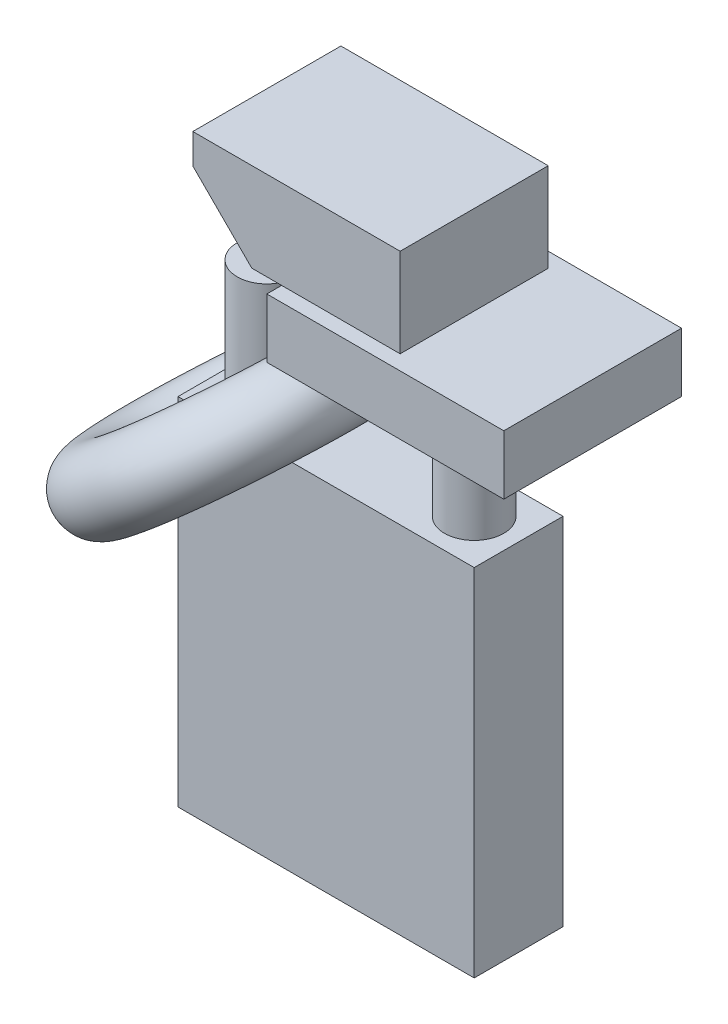
SolidWorks part; units mm, degrees
ref_plane "Front" through (0, 0, 0) normal (0, 0, 1) x (1, 0, 0)
ref_plane "Top" through (0, 0, 0) normal (0, 1, 0) x (1, 0, 0)
ref_plane "Right" through (0, 0, 0) normal (1, 0, 0) x (0, 0, -1)
sketch "Sketch1" plane through (0, 0, 0) normal (0, 0, 1) x (1, 0, 0)
  line L1 (0, 0) -> (31.75, 0)
  line L2 (0, 0) -> (0, 38.1)
  line L3 (0, 38.1) -> (31.75, 38.1)
  line L4 (31.75, 0) -> (31.75, 38.1)
  dimension "D1" = 38.1
  dimension "D2" = 31.75
extrude "Boss-Extrude1" add sketch "Sketch1" along normal mid plane 9.525
sketch "Sketch2" plane through (0, 38.1, 0) normal (0, 1, 0) x (1, 0, 0)
  line L0 (0, -4.7625) -> (0, 4.7625) construction
  line L1 (31.75, -4.7625) -> (31.75, 4.7625) construction
  circle A0 centre (4.7625, 0) radius 3.175
  circle A1 centre (26.9875, 0) radius 3.175
  point P8 (0, 0)
  point P10 (0, 0)
  dimension "D1" = 6.35
  dimension "D2" = 4.7625
  dimension "D3" = 4.7625
extrude "Boss-Extrude2" add sketch "Sketch2" along normal mid plane 25.4
sketch "Sketch3" plane through (0, 0, 0) normal (0, 0, 1) x (1, 0, 0)
  line L0 (26.9875, 50.8) -> (26.9875, 38.1) construction
  line L1 (14.2875, 57.15) -> (39.6875, 57.15)
  line L2 (14.2875, 57.15) -> (14.2875, 50.8)
  line L3 (14.2875, 50.8) -> (39.6875, 50.8)
  line L4 (39.6875, 57.15) -> (39.6875, 50.8)
  line L5 (31.75, 38.1) -> (0, 38.1) construction
  line L6 (30.1625, 50.8) -> (23.8125, 50.8) construction
  point P10 (0, 0)
  dimension "D1" = 6.35
  dimension "D2" = 25.4
extrude "Boss-Extrude3" add sketch "Sketch3" along normal mid plane 19.05
sketch "Sketch4" plane through (0, 0, 0) normal (0, 0, 1) x (1, 0, 0)
  line L0 (26.9875, 57.15) -> (26.9875, 66.675)
  line L1 (39.6875, 57.15) -> (14.2875, 57.15) construction
  line L2 (26.9875, 66.675) -> (4.7625, 66.675)
  line L3 (4.7625, 66.675) -> (4.7625, 63.4746)
  line L4 (4.7625, 63.4746) -> (11.0871, 57.15)
  line L5 (11.0871, 57.15) -> (26.9875, 57.15)
  line L6 (4.7625, 63.4746) -> (11.0871, 63.4746) construction
  line L7 (11.0871, 63.4746) -> (11.0871, 57.15) construction
  point P4 (0, 0)
  point P9 (7.9375, 57.15)
  point P10 (5.0664, 60.0211)
  point P11 (6.3589, 61.8782)
  dimension "D1" = 9.525
  dimension "D2" = 15.9004
  dimension "D3" = 22.225
extrude "Boss-Extrude4" add sketch "Sketch4" along normal mid plane 15.875
sketch "Sketch5" plane through (0, 0, 0) normal (0, 0, 1) x (1, 0, 0)
  line L0 (7.9375, 38.1) -> (7.9375, 50.8) construction
  line L1 (31.75, 38.1) -> (0, 38.1) construction
  line L2 (0, 38.1) -> (31.75, 0) construction
  circle A0 centre (11.9062, 43.18) radius 3.9688
  dimension "D2" = 7.9375
  dimension "D1" = 5.08
revolve "Revolve1" add sketch "Sketch5" angle 360 about L2
